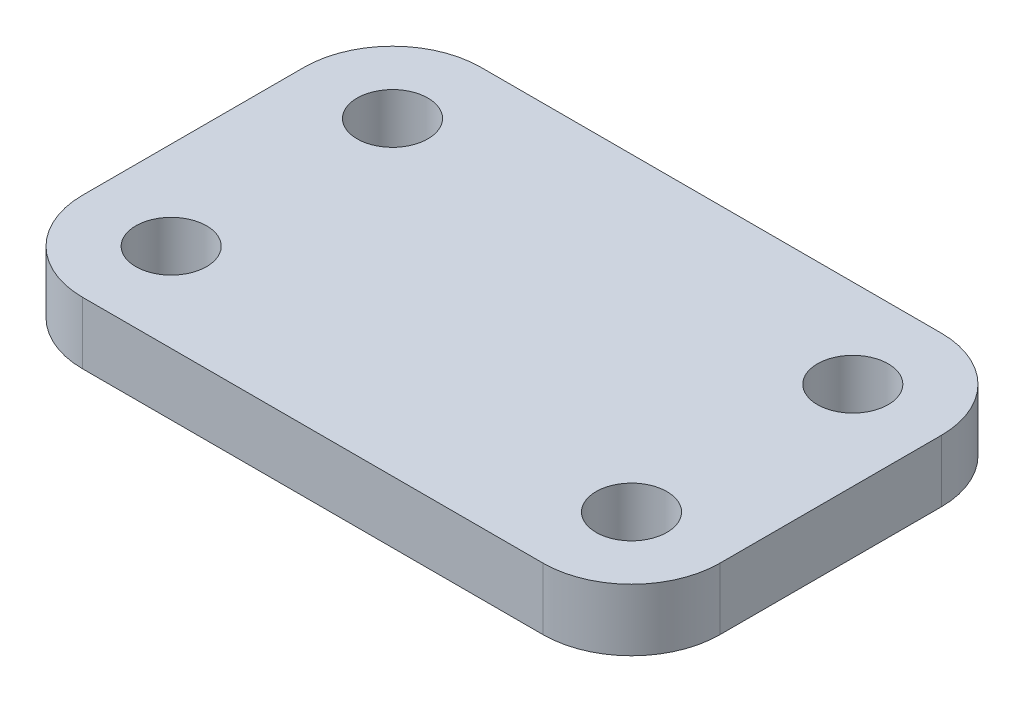
SolidWorks part; units mm, degrees
ref_plane "Alzado" through (0, 0, 0) normal (0, 0, 1) x (1, 0, 0)
ref_plane "Planta" through (0, 0, 0) normal (0, 1, 0) x (1, 0, 0)
ref_plane "Vista lateral" through (0, 0, 0) normal (1, 0, 0) x (0, 0, -1)
sketch "Croquis1" plane through (0, 0, 0) normal (0, 1, 0) x (1, 0, 0)
  line L1 (-36, 22.5) -> (36, 22.5)
  line L2 (-36, 22.5) -> (-36, -22.5)
  line L3 (-36, -22.5) -> (36, -22.5)
  line L4 (36, 22.5) -> (36, -22.5)
  line L5 (-36, 22.5) -> (36, -22.5) construction
  line L6 (-36, -22.5) -> (36, 22.5) construction
  point P0 (0, 0)
  dimension "D1" = 72
  dimension "D2" = 45
extrude "Saliente-Extruir1" add sketch "Croquis1" along normal blind 7
fillet "Redondeo1" radius 10 1 edges at (36, 3.5, 22.5)
fillet "Redondeo2" radius 10 3 edges at (-36, 3.5, -22.5) (-36, 3.5, 22.5) (36, 3.5, -22.5)
sketch "Croquis2" plane through (0, 7, 0) normal (0, 1, 0) x (1, 0, 0)
  circle A0 centre (-26, 12.5) radius 4
  circle A2 centre (-26, -12.5) radius 4
  circle A3 centre (26, -12.5) radius 4
  circle A4 centre (26, 12.5) radius 4
  dimension "D1" = 8
  dimension "D2" = 8
  dimension "D3" = 8
  dimension "D4" = 8
extrude "Cortar-Extruir1" cut sketch "Croquis2" against normal blind 7
